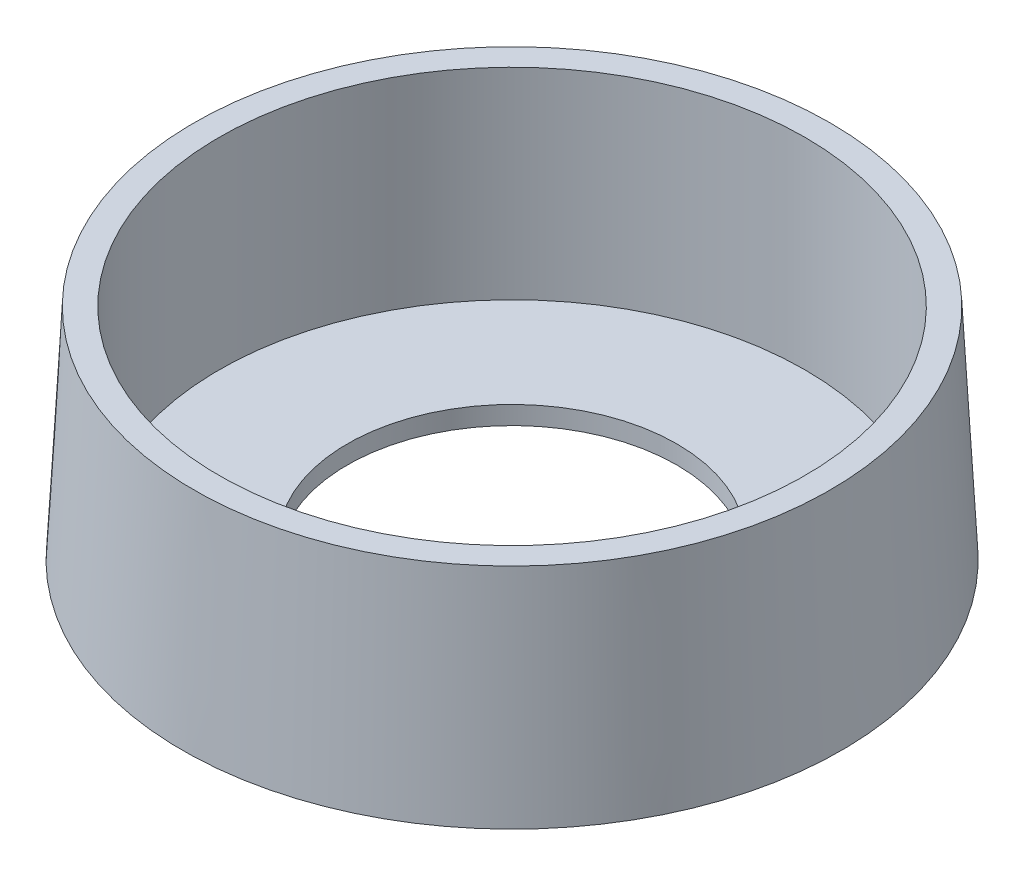
SolidWorks part; units mm, degrees
ref_plane "Front Plane" through (0, 0, 0) normal (0, 0, 1) x (1, 0, 0)
ref_plane "Top Plane" through (0, 0, 0) normal (0, 1, 0) x (1, 0, 0)
ref_plane "Right Plane" through (0, 0, 0) normal (1, 0, 0) x (0, 0, -1)
sketch "Sketch1" plane through (0, 0, 0) normal (1, 0, 0) x (0, 0, -1)
  line L0 (-4.5, 0) -> (-9, 0)
  line L3 (-9, 0) -> (-9, 6)
  line L4 (-9, 6) -> (-8, 6)
  line L5 (-8, 6) -> (-8, 0.5)
  line L6 (-8, 0.5) -> (-4.5, 0.5)
  line L8 (0, 0) -> (0, 5.8251) construction
  line L9 (-4.5, 0.5) -> (-4.5, 0)
  point P2 (-9.1844, 0)
  point P4 (-4.5, 1.8838)
  dimension "D1" = 9
  dimension "D2" = 6
  dimension "D3" = 1
  dimension "D4" = 16
  dimension "D7" = 5.5
revolve "Revolve1" add sketch "Sketch1" angle 360 about L8
draft "Draft1" type of draft neutral plane draft angle 3 faces to draft 1 face at (0, 0, -9) neutral plane through (0, 0, 4.5) neutral plane normal (0, -1, 0) reverse direction yes parameters "D1"=3
